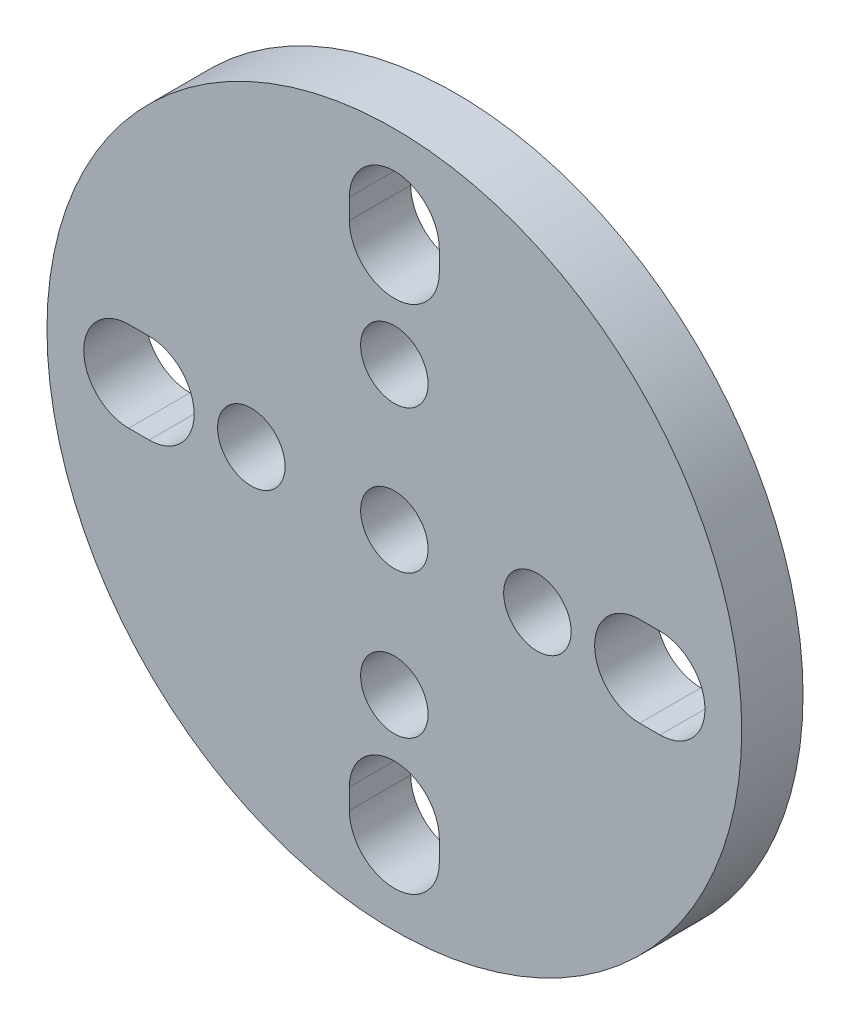
SolidWorks part; units mm, degrees
ref_plane "前视基准面" through (0, 0, 0) normal (0, 0, 1) x (1, 0, 0)
ref_plane "上视基准面" through (0, 0, 0) normal (0, 1, 0) x (1, 0, 0)
ref_plane "右视基准面" through (0, 0, 0) normal (1, 0, 0) x (0, 0, -1)
sketch "草图1" plane through (0, 0, 0) normal (0, 0, 1) x (1, 0, 0)
  line L0 (-13, 2.2) -> (-12, 2.2)
  line L1 (-12, -2.2) -> (-13, -2.2)
  line L2 (-2.2, -13) -> (-2.2, -12)
  line L3 (2.2, -13) -> (2.2, -12)
  line L4 (12, -2.2) -> (13, -2.2)
  line L5 (12, 2.2) -> (13, 2.2)
  line L6 (-2.2, 13) -> (-2.2, 12)
  line L7 (2.2, 13) -> (2.2, 12)
  circle A0 centre (0, 0) radius 17
  circle A1 centre (0, 0) radius 1.65
  circle A3 centre (0, 7) radius 1.65
  circle A4 centre (7, 0) radius 1.65
  circle A5 centre (0, -7) radius 1.65
  circle A6 centre (-7, 0) radius 1.65
  circle A7 centre (0, 13) radius 2.2
  circle A8 centre (0, -13) radius 2.2
  circle A9 centre (13, 0) radius 2.2
  circle A10 centre (-13, 0) radius 2.2
  circle A11 centre (0, 12) radius 2.2
  circle A12 centre (12, 0) radius 2.2
  circle A13 centre (0, -12) radius 2.2
  circle A14 centre (-12, 0) radius 2.2
  dimension "D1" = 26
extrude "凸台-拉伸1" add sketch "草图1" along normal blind 3 contours A0 A14 L1 A10 L0 A13 L3 A8 L2 A12 L5 A9 L4 A11 L6 A7 L7 A6 A5 A4 A3 A1
